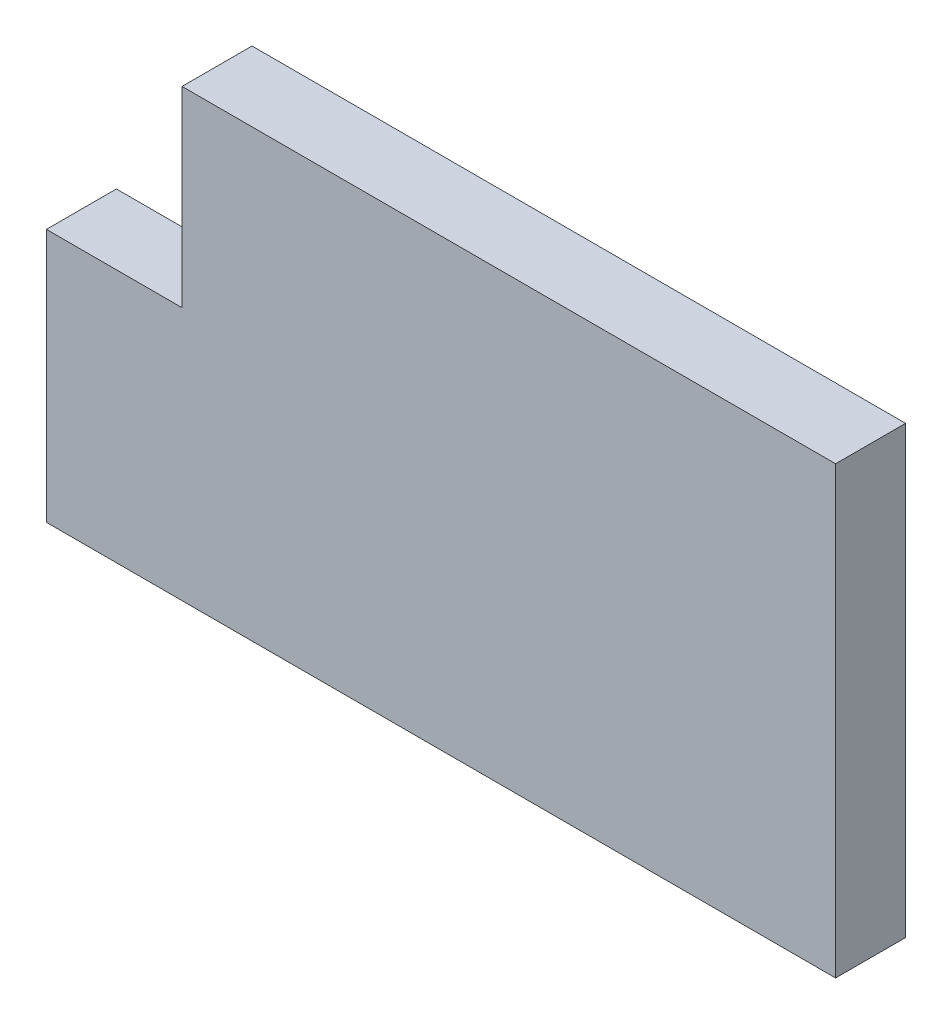
SolidWorks part; units mm, degrees
material "Бетон"
ref_plane "Спереди" through (0, 0, 0) normal (0, 0, 1) x (1, 0, 0)
ref_plane "Сверху" through (0, 0, 0) normal (0, 1, 0) x (1, 0, 0)
ref_plane "Справа" through (0, 0, 0) normal (1, 0, 0) x (0, 0, -1)
sketch "Эскиз1" plane through (0, 0, 0) normal (0, 0, 1) x (1, 0, 0)
  line L9 (906.354, 2129.286) -> (7776.354, 2129.286)
  line L11 (7776.354, 2129.286) -> (8076.354, 2129.286)
  line L12 (8076.354, 2129.286) -> (8076.354, -2660.714)
  line L14 (8076.354, -2660.714) -> (8076.354, -2960.714)
  line L15 (8076.354, -2960.714) -> (-643.646, -2960.714)
  line L17 (-643.646, -2960.714) -> (-943.646, -2960.714)
  line L18 (-943.646, -2960.714) -> (-943.646, -360.714)
  line L20 (906.354, 2129.286) -> (606.354, 2129.286)
  line L21 (606.354, 2129.286) -> (606.354, -60.714)
  line L22 (-943.646, -360.714) -> (-943.646, -60.714)
  line L23 (-943.646, -60.714) -> (606.354, -60.714)
extrude "Бобышка-Вытянуть1" add sketch "Эскиз1" along normal blind 800 contours L21 L23 L22 L18 L17 L15 L14 L12 L11 L9 L20
